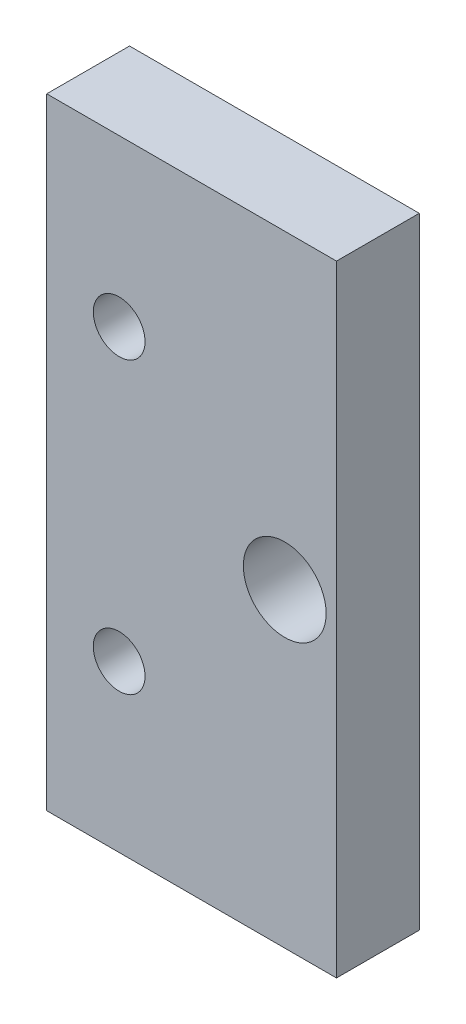
SolidWorks part; units mm, degrees
ref_plane "Front Plane" through (0, 0, 0) normal (0, 0, 1) x (1, 0, 0)
ref_plane "Top Plane" through (0, 0, 0) normal (0, 1, 0) x (1, 0, 0)
ref_plane "Right Plane" through (0, 0, 0) normal (1, 0, 0) x (0, 0, -1)
sketch "Sketch1" plane through (0, 0, 0) normal (0, 0, 1) x (1, 0, 0)
  line L0 (5.715, 0) -> (-4.445, 0) construction
  line L1 (-8.89, -19.05) -> (8.89, -19.05)
  line L2 (-8.89, -19.05) -> (-8.89, 19.05)
  line L3 (-8.89, 19.05) -> (8.89, 19.05)
  line L4 (8.89, -19.05) -> (8.89, 19.05)
  line L5 (-8.89, -19.05) -> (8.89, 19.05) construction
  line L6 (-8.89, 19.05) -> (8.89, -19.05) construction
  line L7 (-4.445, 0) -> (-4.445, 8.89) construction
  line L8 (-4.445, 0) -> (-4.445, -8.89) construction
  circle A0 centre (5.715, 0) radius 2.54
  circle A1 centre (-4.445, 8.89) radius 1.5875
  circle A2 centre (-4.445, -8.89) radius 1.5875
  point P0 (0, 0)
  dimension "D3" = 5.08
  dimension "D7" = 3.175
  dimension "D1" = 17.78
  dimension "D2" = 38.1
  dimension "D4" = 10.16
  dimension "D5" = 3.175
  dimension "D6" = 8.89
extrude "Extrude1" add sketch "Sketch1" along normal blind 5.08
